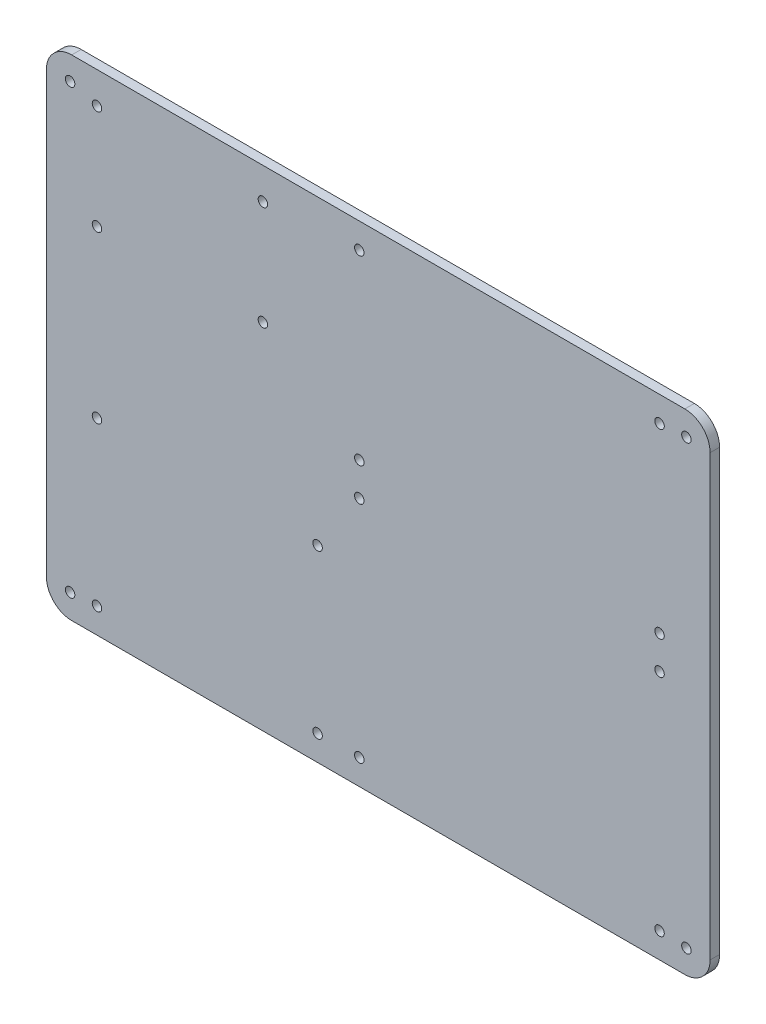
SolidWorks part; units mm, degrees
other "Markup1"
sketch "Sketch6" plane through (-105, -80, 3) normal (0, 0, 1) x (1, 0, 0)
ref_plane "Front Plane" through (0, 0, 0) normal (0, 0, 1) x (1, 0, 0)
ref_plane "Top Plane" through (0, 0, 0) normal (0, 1, 0) x (1, 0, 0)
ref_plane "Right Plane" through (0, 0, 0) normal (1, 0, 0) x (0, 0, -1)
sketch "Sketch1" plane through (0, 0, 0) normal (0, 0, 1) x (1, 0, 0)
  line L1 (-97, 77.5) -> (97, 77.5)
  line L2 (-105, 69.5) -> (-105, -69.5)
  line L3 (-97, -77.5) -> (97, -77.5)
  line L4 (105, 69.5) -> (105, -69.5)
  circle A0 centre (-97.5, 70) radius 1.5
  circle A8 centre (97.5, 70) radius 1.5
  circle A9 centre (-97.5, -70) radius 1.5
  circle A10 centre (97.5, -70) radius 1.5
  arc A11 (97, -77.5) -> (105, -69.5) centre (97, -69.5) ccw
  arc A12 (97, 77.5) -> (105, 69.5) centre (97, 69.5) cw
  arc A13 (-105, -69.5) -> (-97, -77.5) centre (-97, -69.5) ccw
  arc A14 (-97, 77.5) -> (-105, 69.5) centre (-97, 69.5) ccw
  point P17 (105, 77.5)
  point P20 (-105, -77.5)
  point P23 (-105, 77.5)
  dimension "D5" = 3
  dimension "D6" = 6
  dimension "D7" = 6
  dimension "D8" = 3
  dimension "D9" = 6
  dimension "D10" = 6
  dimension "D11" = 6
  dimension "D12" = 6
  dimension "D13" = 3
  dimension "D14" = 3
  dimension "D15" = 6
  dimension "D16" = 6
  dimension "D17" = 8
  dimension "D1" = 210
  dimension "D2" = 155
  dimension "D3" = 77.5
  dimension "D4" = 105
extrude "Boss-Extrude1" add sketch "Sketch1" along normal blind 3
sketch "Sketch2" plane through (0, 0, 3) normal (0, 0, 1) x (1, 0, 0)
  line L1 (-97, 77.5) -> (97, 77.5) construction
  line L2 (105, 69.5) -> (105, -69.5) construction
  circle A0 centre (-6, 69.5) radius 1.5
  circle A1 centre (89, 69.5) radius 1.5
  circle A2 centre (-6, 12) radius 1.5
  circle A3 centre (89, 12) radius 1.5
  dimension "D1" = 3
  dimension "D2" = 3
  dimension "D3" = 3
  dimension "D4" = 3
  dimension "D5" = 95
  dimension "D6" = 57.5
  dimension "D7" = 16
  dimension "D8" = 8
extrude "LVPCB Hole" cut sketch "Sketch2" against normal blind 20
sketch "Sketch4" plane through (0, 0, 3) normal (0, 0, 1) x (1, 0, 0)
  line L0 (-97, -77.5) -> (97, -77.5) construction
  line L1 (105, 69.5) -> (105, -69.5) construction
  circle A0 centre (-6, 1.5) radius 1.5
  circle A1 centre (89, 1.5) radius 1.5
  circle A2 centre (-6, -69.5) radius 1.5
  circle A3 centre (89, -69.5) radius 1.5
  dimension "D1" = 95
  dimension "D2" = 71
  dimension "D3" = 3
  dimension "D4" = 3
  dimension "D5" = 3
  dimension "D6" = 3
  dimension "D7" = 8
  dimension "D8" = 16
extrude "SDC Hole" cut sketch "Sketch4" against normal blind 10
sketch "Sketch3" plane through (0, 0, 3) normal (0, 0, 1) x (1, 0, 0)
  line L0 (-105, 69.5) -> (-105, -69.5) construction
  line L1 (-97, -77.5) -> (97, -77.5) construction
  circle A0 centre (-89, -18) radius 1.5
  circle A1 centre (-19.2, -18) radius 1.5
  circle A2 centre (-89, -69.5) radius 1.5
  circle A3 centre (-19.2, -69.5) radius 1.5
  dimension "D1" = 69.8
  dimension "D2" = 51.5
  dimension "D3" = 3
  dimension "D4" = 3
  dimension "D5" = 3
  dimension "D6" = 3
  dimension "D7" = 16
  dimension "D8" = 8
extrude "TSAL LV Hole" cut sketch "Sketch3" against normal blind 10 contours A0 | A1 | A3 | A2
sketch "Sketch5" plane through (0, 0, 3) normal (0, 0, 1) x (1, 0, 0)
  line L2 (-105, 69.5) -> (-105, -69.5) construction
  line L3 (-97, 77.5) -> (97, 77.5) construction
  circle A0 centre (-89, 67.5) radius 1.5
  circle A1 centre (-36.5, 67.5) radius 1.5
  circle A2 centre (-89, 34.5) radius 1.5
  circle A3 centre (-36.5, 34.5) radius 1.5
  dimension "D1" = 52.5
  dimension "D2" = 33
  dimension "D3" = 16
  dimension "D4" = 10
  dimension "D5" = 3
  dimension "D6" = 3
  dimension "D7" = 3
  dimension "D8" = 3
extrude "BSPD Hole" cut sketch "Sketch5" against normal blind 10
